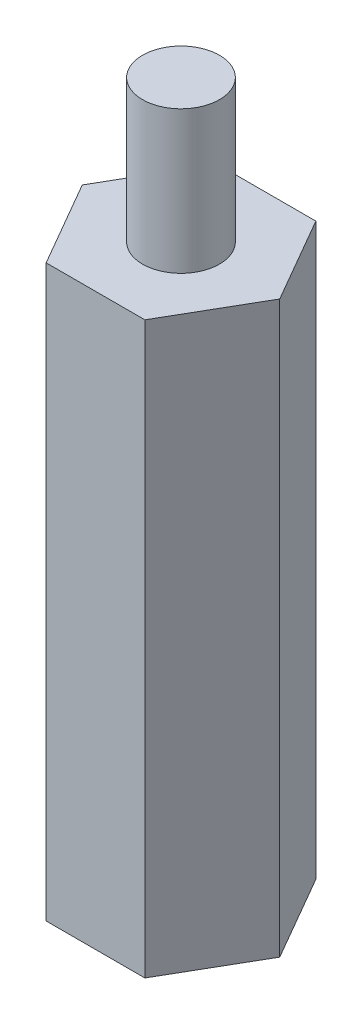
SolidWorks part; units mm, degrees
ref_plane "정면도" through (0, 0, 0) normal (0, 0, 1) x (1, 0, 0)
ref_plane "평면도" through (0, 0, 0) normal (0, 1, 0) x (1, 0, 0)
ref_plane "우측면도" through (0, 0, 0) normal (1, 0, 0) x (0, 0, -1)
sketch "스케치1" plane through (0, 0, 0) normal (0, 1, 0) x (1, 0, 0)
  line L1 (3.4641, 0) -> (1.7321, 3)
  line L2 (1.7321, 3) -> (-1.7321, 3)
  line L3 (-1.7321, 3) -> (-3.4641, 0)
  line L4 (-3.4641, 0) -> (-1.7321, -3)
  line L5 (-1.7321, -3) -> (1.7321, -3)
  line L6 (1.7321, -3) -> (3.4641, 0)
  circle A0 centre (0, 0) radius 3 construction
  dimension "D1" = 6
extrude "보스-돌출1" add sketch "스케치1" along normal blind 20
sketch "스케치2" plane through (0, 20, 0) normal (0, 1, 0) x (1, 0, 0)
  circle A0 centre (0, 0) radius 1.35
  dimension "D1" = 2.7
extrude "보스-돌출2" add sketch "스케치2" along normal blind 5
sketch "스케치3" plane through (0, 0, 0) normal (0, -1, 0) x (1, 0, 0)
  circle A0 centre (0, 0) radius 1.35
  dimension "D1" = 2.7
extrude "컷-돌출1" cut sketch "스케치3" against normal blind 4
